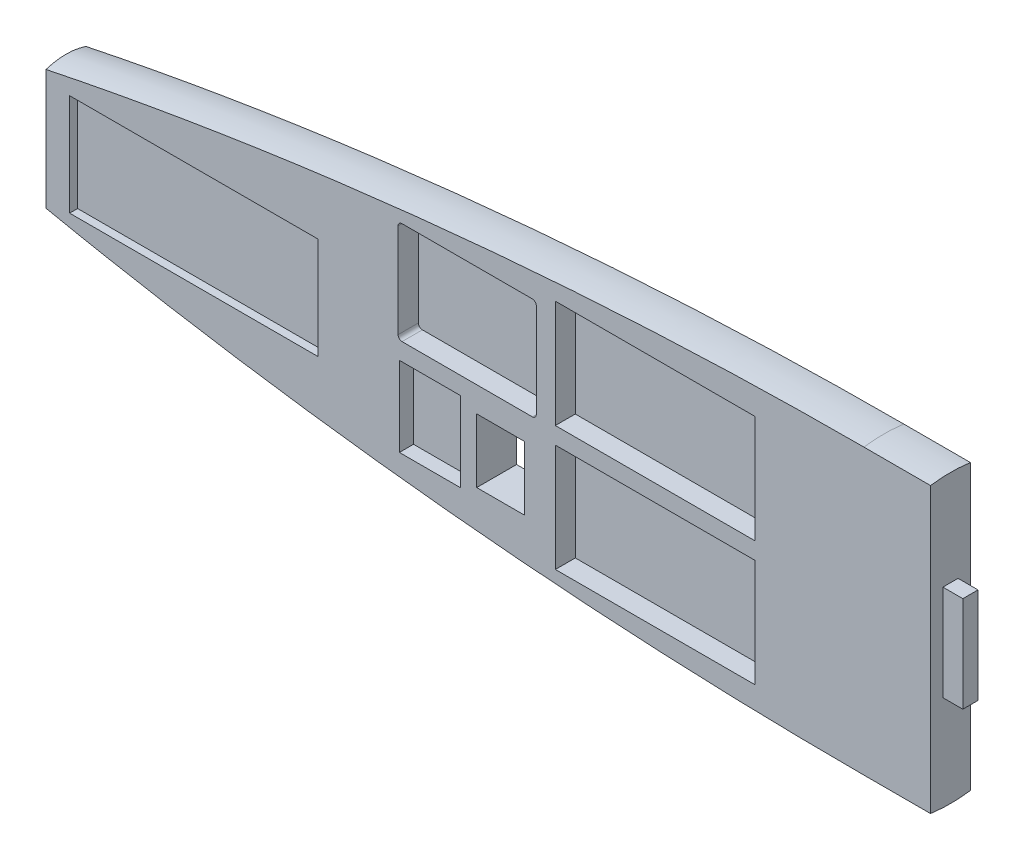
SolidWorks part; units mm, degrees
ref_plane "Front Plane" through (0, 0, 0) normal (0, 0, 1) x (1, 0, 0)
ref_plane "Top Plane" through (0, 0, 0) normal (0, 1, 0) x (1, 0, 0)
ref_plane "Right Plane" through (0, 0, 0) normal (1, 0, 0) x (0, 0, -1)
sketch "Sketch3" plane through (0, 0, 0) normal (0, 0, 1) x (1, 0, 0)
  line L0 (285.7488, 39.71) -> (285.7488, 3.758)
  line L1 (285.7488, 3.758) -> (80.7488, 3.758)
  line L2 (80.7488, 3.758) -> (80.7488, 19.6343)
  spline S0 degree 4 poles (-27.7192, -7.8553) (-27.5014, -7.7876) (-27.0667, -7.6528) (-26.2045, -7.3856) (-24.4548, -6.8463) (-22.0886, -6.1211) (-19.0086, -5.1883) (-15.5879, -4.1634) (-12.0469, -3.1177) (-8.7154, -2.1438) (-5.4871, -1.2149) (-3.2266, -0.5688) (-0.5536, 0.1859) (0.4881, 0.4785) (2.6576, 1.0849) (4.0523, 1.4709) (5.8579, 1.9693) (7.4437, 2.403) (9.5599, 2.9792) (12.0305, 3.6454) (14.9574, 4.4267) (18.2801, 5.3017) (21.6183, 6.1694) (25.7869, 7.2382) (30.7991, 8.5003) (35.8155, 9.7344) (40.8401, 10.9416) (45.8691, 12.1268) (50.9036, 13.2902) (56.7842, 14.6155) (65.1975, 16.4541) (73.6264, 18.2195) (82.0703, 19.9115) (92.2203, 21.8537) (109.1645, 24.9437) (127.868, 27.9778) (146.6331, 30.6047) (163.7338, 32.6585) (174.0045, 33.8015) (184.2848, 34.8552) (194.5761, 35.7972) (204.8769, 36.6272) (213.4665, 37.2443) (220.3412, 37.6932) (227.2189, 38.0972) (233.2386, 38.4115) (238.4005, 38.6528) (242.7017, 38.8352) (246.1452, 38.9699) (249.585, 39.0934) (253.0324, 39.2057) (256.468, 39.3067) (259.9241, 39.3966) (263.347, 39.4752) (266.8257, 39.5425) (270.2119, 39.5987) (273.7565, 39.6436) (276.6051, 39.6731) (279.4395, 39.6913) (281.5976, 39.7039) (285.1517, 39.711) (286.4225, 39.7109) (289.9962, 39.7036) (293.1094, 39.6857) (296.9947, 39.6557) (300.782, 39.6062) (305.3918, 39.5309) (308.4492, 39.4673) (311.2049, 39.4051) (312.9634, 39.3595) (313.8789, 39.3357) (314.3251, 39.3236) knots 0 0 0 0 0 0.00262 0.00524 0.01048 0.02096 0.03144 0.041921 0.052275 0.06263 0.072985 0.078162 0.083339 0.088305 0.093271 0.098237 0.103203 0.108168 0.113134 0.123066 0.132998 0.142929 0.152861 0.162793 0.182656 0.20252 0.212451 0.222383 0.242246 0.26211 0.281973 0.3217 0.341563 0.361427 0.401154 0.520334 0.560061 0.579924 0.599788 0.639515 0.679241 0.699105 0.718968 0.738832 0.758695 0.778558 0.78849 0.798422 0.808354 0.818285 0.828217 0.838149 0.84808 0.858012 0.867944 0.877875 0.887807 0.897739 0.902705 0.907671 0.917602 0.927839 0.932958 0.938076 0.95855 0.968912 0.979275 0.989637 0.994819 1 1 1 1 1 construction
  spline S1 degree 4 poles (80.7488, 19.6343) (82.3471, 19.9504) (85.6364, 20.5939) (92.3118, 21.8704) (109.1645, 24.9437) (127.868, 27.9778) (146.6331, 30.6047) (163.7338, 32.6585) (174.0045, 33.8015) (184.2848, 34.8552) (194.5761, 35.7972) (204.8769, 36.6272) (213.4665, 37.2443) (220.3412, 37.6932) (227.2189, 38.0972) (233.2386, 38.4115) (238.4005, 38.6528) (242.7017, 38.8352) (246.1452, 38.9699) (249.585, 39.0934) (253.0324, 39.2057) (256.468, 39.3067) (259.9241, 39.3966) (263.347, 39.4752) (266.8257, 39.5425) (270.2119, 39.5987) (273.7565, 39.6436) (276.6051, 39.6731) (279.4395, 39.6913) (281.5976, 39.7039) (283.943, 39.7086) (285.0303, 39.71) (285.7488, 39.71) knots 0.322773 0.322773 0.322773 0.322773 0.322773 0.341563 0.361427 0.401154 0.520334 0.560061 0.579924 0.599788 0.639515 0.679241 0.699105 0.718968 0.738832 0.758695 0.778558 0.78849 0.798422 0.808354 0.818285 0.828217 0.838149 0.84808 0.858012 0.867944 0.877875 0.887807 0.897739 0.902705 0.907671 0.917602 0.917602 0.917602 0.917602 0.917602
  dimension "D1" = 35.952
  dimension "D2" = 205
revolve "Revolve1" add sketch "Sketch3" angle 360 about L1
sketch "Sketch6" plane through (285.7488, 0, 0) normal (1, 0, 0) x (0, 0, -1)
  line L5 (-5, 39.67) -> (5, 39.67)
  line L6 (-5, 39.67) -> (-5, -32.154)
  line L15 (-5, -32.154) -> (5, -32.154)
  line L16 (5, 39.67) -> (5, -32.154)
  line L17 (0, -32.154) -> (0, 39.67) construction
  line L18 (-5, 3.758) -> (5, 3.758) construction
  line L19 (5, -32.154) -> (36.0764, -32.154)
  line L20 (5, -32.154) -> (5, 39.67)
  line L21 (5, 39.67) -> (36.0764, 39.67)
  line L22 (36.0764, -32.154) -> (36.0764, 39.67)
  line L23 (-5, 39.67) -> (-36.0314, 39.67)
  line L24 (-5, 39.67) -> (-5, -32.154)
  line L25 (-5, -32.154) -> (-36.0314, -32.154)
  line L26 (-36.0314, 39.67) -> (-36.0314, -32.154)
  point P0 (0, 3.758)
  point P1 (0, 3.758)
  circle M5 centre (0, 3.758) radius 35.952
  dimension "D1" = 5
extrude "Cut-Extrude1" cut sketch "Sketch6" against normal through all contours L6 M5 | L16 M5
sketch "Sketch8" plane through (285.7488, 0, 0) normal (1, 0, 0) x (0, 0, -1)
  line L0 (5, 39.3606) -> (5, -31.8446)
  line L6 (-5, -31.8446) -> (-5, 39.3606)
  circle A2 centre (0, 3.758) radius 35.952
  arc M19 (5, 39.3606) -> (-5, 39.3606) centre (0, 3.758) ccw
  line M20 (-5, 39.3606) -> (-5, -31.8446)
  arc M21 (-5, -31.8446) -> (5, -31.8446) centre (0, 3.758) ccw
  line M22 (5, -31.8446) -> (5, 39.3606)
  dimension "D1" = 71.904
extrude "Boss-Extrude2" add sketch "Sketch8" along normal blind 139.7 contours M22 M19 M20 M21
sketch "Sketch9" plane through (425.4488, 0, 0) normal (1, 0, 0) x (0, 0, -1)
  circle A1 centre (0, 3.758) radius 35.952
  dimension "D1" = 71.904
extrude "Boss-Extrude3" add sketch "Sketch9" along normal blind 4
sketch "Sketch10" plane through (429.4488, 0, 0) normal (1, 0, 0) x (0, 0, -1)
  line L4 (-17, -4.442) -> (-17, 11.958)
  line L5 (-8.2, 20.758) -> (8.2, 20.758)
  line L6 (17, 11.958) -> (17, -4.442)
  line L7 (8.2, -13.242) -> (-8.2, -13.242)
  line L8 (-17, 11.958) -> (-8.2, 20.758)
  line L9 (8.2, 20.758) -> (17, 11.958)
  line L10 (17, -4.442) -> (8.2, -13.242)
  line L11 (-8.2, -13.242) -> (-17, -4.442)
  dimension "D5" = 16.4
  dimension "D7" = 16.4
  dimension "D9" = 16.4
  dimension "D11" = 16.4
extrude "Cut-Extrude2" cut sketch "Sketch10" against normal blind 4
sketch "Sketch11" plane through (425.4488, 0, 0) normal (1, 0, 0) x (0, 0, -1)
  line L1 (-5, 20.758) -> (5, 20.758)
  line L2 (-5, 20.758) -> (-5, -13.242)
  line L3 (-5, -13.242) -> (5, -13.242)
  line L4 (5, 20.758) -> (5, -13.242)
  line L5 (0, -13.242) -> (0, 20.758) construction
  line L6 (-5, 3.758) -> (5, 3.758) construction
  point P0 (0, 3.758)
extrude "Cut-Extrude3" cut sketch "Sketch11" against normal blind 15
sketch "Sketch12" plane through (0, 0, 5) normal (0, 0, 1) x (1, 0, 0)
  line L1 (404.4488, -22.6113) -> (321.4488, -22.6113)
  line L2 (405.4488, -21.6113) -> (405.4488, 32.3887)
  line L3 (404.4488, 33.3887) -> (321.4488, 33.3887)
  line L4 (320.4488, -21.6113) -> (320.4488, 32.3887)
  arc A0 (320.4488, -21.6113) -> (321.4488, -22.6113) centre (321.4488, -21.6113) ccw
  arc A1 (404.4488, -22.6113) -> (405.4488, -21.6113) centre (404.4488, -21.6113) ccw
  arc A2 (405.4488, 32.3887) -> (404.4488, 33.3887) centre (404.4488, 32.3887) ccw
  arc A3 (321.4488, 33.3887) -> (320.4488, 32.3887) centre (321.4488, 32.3887) ccw
  point P10 (320.4488, -22.6113)
  point P13 (405.4488, -22.6113)
  point P16 (405.4488, 33.3887)
  dimension "D5" = 1
  dimension "D3" = 85
  dimension "D4" = 56
extrude "Raspberry Pi 5" cut sketch "Sketch12" against normal blind 5 contours A3 L3 A2 L2 A1 L1 A0 L4
sketch "Sketch13" plane through (0, 0, 5) normal (0, 0, 1) x (1, 0, 0)
  line L1 (202.6366, 4.3734) -> (169.9866, 4.3734)
  line L2 (203.6366, 5.3734) -> (203.6366, 28.9734)
  line L3 (202.6366, 29.9734) -> (169.9866, 29.9734)
  line L4 (168.9866, 5.3734) -> (168.9866, 28.9734)
  arc A0 (202.6366, 29.9734) -> (203.6366, 28.9734) centre (202.6366, 28.9734) cw
  arc A1 (203.6366, 5.3734) -> (202.6366, 4.3734) centre (202.6366, 5.3734) cw
  arc A2 (168.9866, 5.3734) -> (169.9866, 4.3734) centre (169.9866, 5.3734) ccw
  arc A3 (169.9866, 29.9734) -> (168.9866, 28.9734) centre (169.9866, 28.9734) ccw
  point P12 (203.6366, 4.3734)
  point P15 (168.9866, 4.3734)
  point P18 (168.9866, 29.9734)
  dimension "D5" = 1
  dimension "D1" = 34.65
  dimension "D2" = 25.6
extrude "GPS Slot" cut sketch "Sketch13" against normal blind 5.1
sketch "Sketch14" plane through (0, 0, 5) normal (0, 0, 1) x (1, 0, 0)
  line L1 (188.7017, -1.9519) -> (200.7017, -1.9519)
  line L2 (188.7017, -1.9519) -> (188.7017, -17.9519)
  line L3 (188.7017, -17.9519) -> (200.7017, -17.9519)
  line L4 (200.7017, -1.9519) -> (200.7017, -17.9519)
  line L5 (194.7017, -17.9519) -> (194.7017, -1.9519) construction
  line L6 (188.7017, -9.9519) -> (200.7017, -9.9519) construction
  point P0 (194.7017, -9.9519)
  point P4 (284.8721, -20.318)
  point P5 (289.2258, -3.916)
  point P6 (194.7017, -9.9519)
  dimension "D1" = 12
  dimension "D2" = 16
extrude "MPU" cut sketch "Sketch14" against normal through all
sketch "Sketch15" plane through (0, 0, 5) normal (0, 0, 1) x (1, 0, 0)
  line L1 (169.3203, -0.0172) -> (184.6603, -0.0172)
  line L2 (169.3203, -0.0172) -> (169.3203, -20.0172)
  line L3 (169.3203, -20.0172) -> (184.6603, -20.0172)
  line L4 (184.6603, -0.0172) -> (184.6603, -20.0172)
  line L5 (176.9903, -20.0172) -> (176.9903, -0.0172) construction
  line L6 (169.3203, -10.0172) -> (184.6603, -10.0172) construction
  point P0 (176.9903, -10.0172)
  point P4 (286.0962, -1.5954)
  point P5 (269.275, -4.6298)
  point P6 (271.0562, -4.6464)
  point P7 (176.9903, -10.0172)
  dimension "D1" = 15.34
  dimension "D2" = 20
extrude "Altimeter" cut sketch "Sketch15" against normal blind 3.54 and the other way through all
sketch "Sketch16" plane through (0, 0, 5) normal (0, 0, 1) x (1, 0, 0)
  line L1 (86.6751, 16.0984) -> (148.8751, 16.0984)
  line L2 (86.6751, 16.0984) -> (86.6751, -9.4016)
  line L3 (86.6751, -9.4016) -> (148.8751, -9.4016)
  line L4 (148.8751, 16.0984) -> (148.8751, -9.4016)
  line L5 (117.7751, -9.4016) -> (117.7751, 16.0984) construction
  line L6 (86.6751, 3.3484) -> (148.8751, 3.3484) construction
  point P0 (117.7751, 3.3484)
  point P4 (117.7751, 3.3484)
  dimension "D1" = 62.2
  dimension "D2" = 25.5
extrude "PCA9685" cut sketch "Sketch16" against normal blind 2
sketch "Sketch17" plane through (0, 0, 5) normal (0, 0, 1) x (1, 0, 0)
  line L1 (208.4148, 1.1255) -> (258.4148, 1.1255)
  line L2 (208.4148, 1.1255) -> (208.4148, -25.8745)
  line L3 (208.4148, -25.8745) -> (258.4148, -25.8745)
  line L4 (258.4148, 1.1255) -> (258.4148, -25.8745)
  line L5 (233.4148, -25.8745) -> (233.4148, 1.1255) construction
  line L6 (208.4148, -12.3745) -> (258.4148, -12.3745) construction
  point P0 (233.4148, -12.3745)
  point P4 (233.4148, -12.3745)
  dimension "D1" = 50
  dimension "D2" = 27
extrude "ESP-32 (1)" cut sketch "Sketch17" against normal blind 5
sketch "Sketch18" plane through (0, 0, -5) normal (0, 0, -1) x (-1, 0, 0)
  line L1 (-350.4488, 35.0173) -> (-405.4488, 35.0173)
  line L2 (-350.4488, 35.0173) -> (-350.4488, 4.9173)
  line L3 (-350.4488, 4.9173) -> (-405.4488, 4.9173)
  line L4 (-405.4488, 35.0173) -> (-405.4488, 4.9173)
  line L5 (-377.9488, 4.9173) -> (-377.9488, 35.0173) construction
  line L6 (-350.4488, 19.9673) -> (-405.4488, 19.9673) construction
  point P0 (-377.9488, 19.9673)
  dimension "D1" = 55
  dimension "D2" = 30.1
sketch "Sketch21" plane through (0, 0, -5) normal (0, 0, -1) x (-1, 0, 0)
  line L1 (-350.4488, 2.5987) -> (-405.4488, 2.5987)
  line L2 (-350.4488, 2.5987) -> (-350.4488, -27.5013)
  line L3 (-350.4488, -27.5013) -> (-405.4488, -27.5013)
  line L4 (-405.4488, 2.5987) -> (-405.4488, -27.5013)
  line L5 (-377.9488, -27.5013) -> (-377.9488, 2.5987) construction
  line L6 (-350.4488, -12.4513) -> (-405.4488, -12.4513) construction
  point P0 (-377.9488, -12.4513)
  dimension "D1" = 55
  dimension "D2" = 30.1
extrude "Battery 1" cut sketch "Sketch18" against normal blind 3.5
extrude "Battery 2" cut sketch "Sketch21" against normal blind 3.5
sketch "Sketch25" plane through (0, 0, -5) normal (0, 0, -1) x (-1, 0, 0)
  line L1 (-334.5276, 27.4269) -> (-313.4276, 27.4269)
  line L2 (-334.5276, 27.4269) -> (-334.5276, -15.6731)
  line L3 (-334.5276, -15.6731) -> (-313.4276, -15.6731)
  line L4 (-313.4276, 27.4269) -> (-313.4276, -15.6731)
  line L5 (-323.9776, -15.6731) -> (-323.9776, 27.4269) construction
  line L6 (-334.5276, 5.8769) -> (-313.4276, 5.8769) construction
  point P0 (-323.9776, 5.8769)
  dimension "D1" = 43.1
  dimension "D2" = 21.1
extrude "Step Down" cut sketch "Sketch25" against normal blind 1
sketch "Sketch27" plane through (429.4488, 0, 0) normal (1, 0, 0) x (0, 0, -1)
  circle A0 centre (0, 3.758) radius 36.3
  circle A1 centre (0, 3.758) radius 30
  dimension "D1" = 72.6
extrude "Boss-Extrude4" add sketch "Sketch27" against normal blind 7 from offset 120 offset against normal yes
sketch "Sketch28" plane through (429.4488, 0, 0) normal (1, 0, 0) x (0, 0, -1)
  circle A0 centre (0, 3.758) radius 36.3
extrude "Cut-Extrude4" cut sketch "Sketch28" along normal through all from offset 127 offset against normal yes
sketch "Sketch29" plane through (302.4488, 0, 0) normal (1, 0, 0) x (0, 0, -1)
  line L1 (-1.9, 15.758) -> (1.9, 15.758)
  line L2 (-1.9, 15.758) -> (-1.9, -8.242)
  line L3 (-1.9, -8.242) -> (1.9, -8.242)
  line L4 (1.9, 15.758) -> (1.9, -8.242)
  line L5 (0, -8.242) -> (0, 15.758) construction
  line L6 (-1.9, 3.758) -> (1.9, 3.758) construction
  point P0 (0, 3.758)
  dimension "D1" = 1.9
  dimension "D2" = 12
extrude "Boss-Extrude5" add sketch "Sketch29" along normal blind 5
sketch "Sketch33" plane through (0, 0, 5) normal (0, 0, 1) x (1, 0, 0)
  line L1 (208.4062, 32.3643) -> (258.4062, 32.3643)
  line L2 (208.4062, 32.3643) -> (208.4062, 5.3643)
  line L3 (208.4062, 5.3643) -> (258.4062, 5.3643)
  line L4 (258.4062, 32.3643) -> (258.4062, 5.3643)
  line L5 (233.4062, 5.3643) -> (233.4062, 32.3643) construction
  line L6 (208.4062, 18.8643) -> (258.4062, 18.8643) construction
  point P0 (233.4062, 18.8643)
  point P4 (233.3486, 21.0857)
  point P5 (233.4062, 18.8643)
  dimension "D1" = 50
  dimension "D2" = 27
extrude "ESP-32 (2)" cut sketch "Sketch33" against normal blind 5
